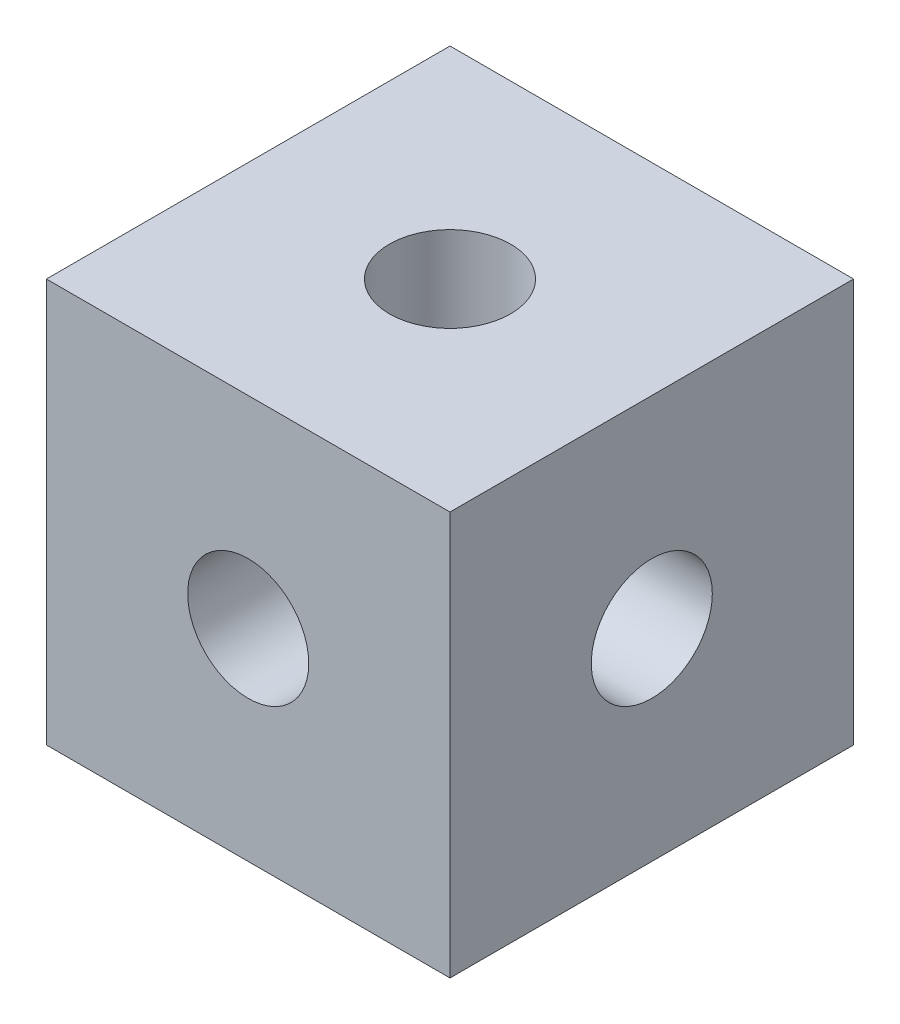
SolidWorks part; units mm, degrees
ref_plane "前视基准面" through (0, 0, 0) normal (0, 0, 1) x (1, 0, 0)
ref_plane "上视基准面" through (0, 0, 0) normal (0, 1, 0) x (1, 0, 0)
ref_plane "右视基准面" through (0, 0, 0) normal (1, 0, 0) x (0, 0, -1)
other "Configuration Table"
sketch "草图1" plane through (0, 0, 0) normal (1, 0, 0) x (0, 0, -1)
  line L1 (0, 0) -> (10, 0)
  line L2 (0, 0) -> (0, 10)
  line L3 (0, 10) -> (10, 10)
  line L4 (10, 0) -> (10, 10)
  dimension "D1" = 10
  dimension "D2" = 10
extrude "凸台-拉伸1" add sketch "草图1" along normal blind 10
sketch "草图2" plane through (0, 10, 0) normal (0, 1, 0) x (1, 0, 0)
  line L2 (5, 10) -> (5, 8.3002) construction
  line L3 (10, 10) -> (0, 10) construction
  line L4 (0, 5) -> (0.6572, 5) construction
  line L5 (0, 10) -> (0, 0) construction
  circle A0 centre (5, 5) radius 1.5
  dimension "D1" = 3
extrude "切除-拉伸1" cut sketch "草图2" against normal blind 12
sketch "草图3" plane through (0, 0, 0) normal (0, 0, 1) x (1, 0, 0)
  line L2 (5, 10) -> (5, 8.6981) construction
  line L3 (10, 10) -> (0, 10) construction
  line L4 (0, 5) -> (0.6347, 5) construction
  line L5 (0, 10) -> (0, 0) construction
  circle A0 centre (5, 5) radius 1.5
  dimension "D3" = 3
extrude "切除-拉伸2" cut sketch "草图3" against normal blind 12
sketch "草图4" plane through (10, 0, 0) normal (1, 0, 0) x (0, 0, -1)
  line L0 (0, 5) -> (1.5735, 5) construction
  line L1 (0, 10) -> (0, 0) construction
  line L2 (5, 10) -> (5, 10.2281) construction
  line L3 (10, 10) -> (0, 10) construction
  circle A0 centre (5, 5) radius 1.5
  dimension "D1" = 3
extrude "切除-拉伸3" cut sketch "草图4" against normal blind 11
